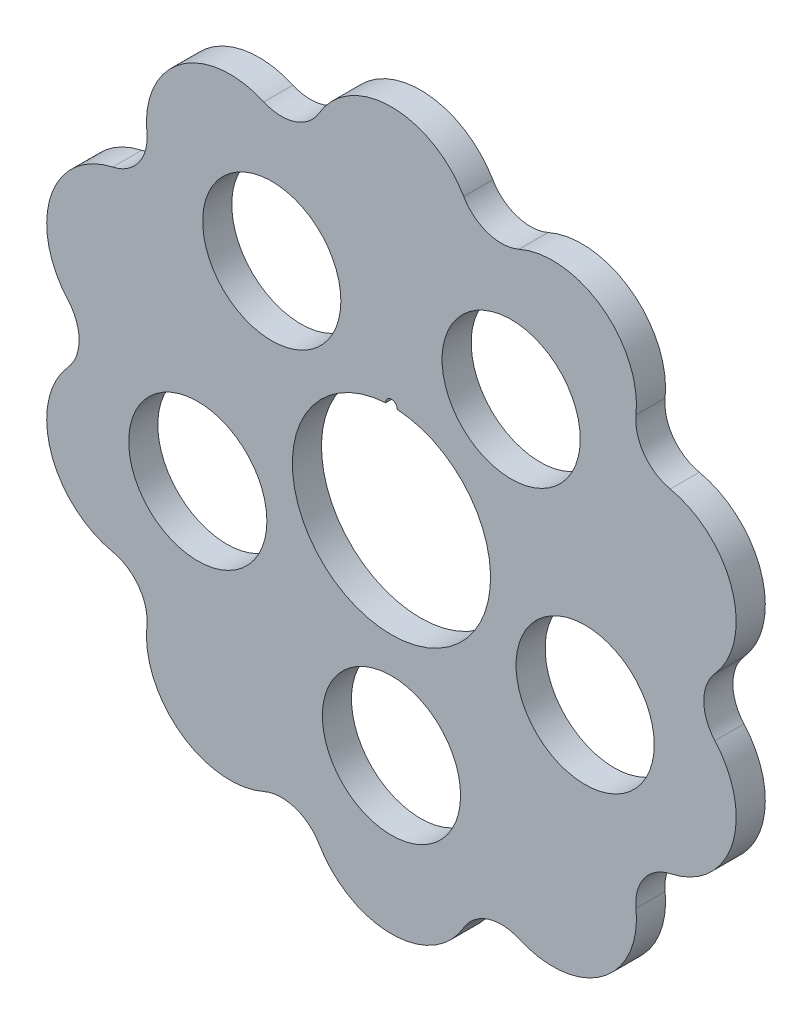
SolidWorks part; units mm, degrees
ref_plane "前视基准面" through (0, 0, 0) normal (0, 0, 1) x (1, 0, 0)
ref_plane "上视基准面" through (0, 0, 0) normal (0, 1, 0) x (1, 0, 0)
ref_plane "右视基准面" through (0, 0, 0) normal (1, 0, 0) x (0, 0, -1)
sketch "草图1" plane through (0, 0, 0) normal (0, 0, 1) x (1, 0, 0)
  line L0 (0, -37.75) -> (22.1889, -30.5404) construction
  line L1 (0, 0) -> (11.0944, -34.1452) construction
  line L2 (11.0944, -34.1452) -> (15.711, -48.3534) construction
  line L3 (0, 0) -> (0, -63.6583) construction
  line L4 (-15.1255, -46.5516) -> (0, -37.75) construction
  line L5 (0, -37.75) -> (15.1255, -46.5516) construction
  circle A0 centre (0, 0) radius 13.625
  circle A1 centre (0, 0) radius 28 construction
  circle A2 centre (0, -28) radius 9.5
  circle A3 centre (-26.6296, -8.6525) radius 9.5
  circle A4 centre (-16.458, 22.6525) radius 9.5
  circle A5 centre (16.458, 22.6525) radius 9.5
  circle A6 centre (26.6296, -8.6525) radius 9.5
  circle A7 centre (0, 0) radius 37.75 construction
  circle A8 centre (0, -37.75) radius 11.5 construction
  circle A9 centre (-22.1889, -30.5404) radius 11.5 construction
  circle A10 centre (-15.1255, -46.5516) radius 6 construction
  arc A11 (-9.9396, -43.5339) -> (9.9396, -43.5339) centre (0, -37.75) ccw
  arc A12 (9.9396, -43.5339) -> (17.5473, -41.062) centre (15.1255, -46.5516) cw
  arc A13 (-33.6299, -29.3773) -> (-17.5473, -41.062) centre (-22.1889, -30.5404) ccw
  arc A14 (-17.5473, -41.062) -> (-9.9396, -43.5339) centre (-15.1255, -46.5516) cw
  arc A15 (-44.4747, -3.9996) -> (-38.3317, -22.9059) centre (-35.9024, -11.6654) ccw
  arc A16 (-38.3317, -22.9059) -> (-33.6299, -29.3773) centre (-39.5992, -28.7705) cw
  circle A17 centre (22.1889, -30.5404) radius 11.5 construction
  circle A18 centre (0, 0) radius 42.61 construction
  circle A19 centre (15.1255, -46.5516) radius 6 construction
  circle A20 centre (35.9024, -11.6654) radius 11.5 construction
  circle A21 centre (35.9024, 11.6654) radius 11.5 construction
  circle A22 centre (22.1889, 30.5404) radius 11.5 construction
  circle A23 centre (0, 37.75) radius 11.5 construction
  circle A24 centre (-22.1889, 30.5404) radius 11.5 construction
  circle A25 centre (-35.9024, 11.6654) radius 11.5 construction
  circle A26 centre (-35.9024, -11.6654) radius 11.5 construction
  arc A27 (-38.3317, 22.9059) -> (-44.4747, 3.9996) centre (-35.9024, 11.6654) ccw
  arc A28 (-44.4747, 3.9996) -> (-44.4747, -3.9996) centre (-48.9473, 0) cw
  arc A29 (-17.5473, 41.062) -> (-33.6299, 29.3773) centre (-22.1889, 30.5404) ccw
  arc A30 (-33.6299, 29.3773) -> (-38.3317, 22.9059) centre (-39.5992, 28.7705) cw
  arc A31 (9.9396, 43.5339) -> (-9.9396, 43.5339) centre (0, 37.75) ccw
  arc A32 (-9.9396, 43.5339) -> (-17.5473, 41.062) centre (-15.1255, 46.5516) cw
  arc A33 (33.6299, 29.3773) -> (17.5473, 41.062) centre (22.1889, 30.5404) ccw
  arc A34 (17.5473, 41.062) -> (9.9396, 43.5339) centre (15.1255, 46.5516) cw
  arc A35 (44.4747, 3.9996) -> (38.3317, 22.9059) centre (35.9024, 11.6654) ccw
  arc A36 (38.3317, 22.9059) -> (33.6299, 29.3773) centre (39.5992, 28.7705) cw
  arc A37 (38.3317, -22.9059) -> (44.4747, -3.9996) centre (35.9024, -11.6654) ccw
  arc A38 (44.4747, -3.9996) -> (44.4747, 3.9996) centre (48.9473, 0) cw
  arc A39 (17.5473, -41.062) -> (33.6299, -29.3773) centre (22.1889, -30.5404) ccw
  arc A40 (33.6299, -29.3773) -> (38.3317, -22.9059) centre (39.5992, -28.7705) cw
  dimension "D1" = 27.25
  dimension "D2" = 56
  dimension "D3" = 19
  dimension "D5" = 23
  dimension "D6" = 75.5
  dimension "D8" = 85.22
  dimension "D9" = 12
  dimension "D4" = 5
  dimension "D7" = 10
  dimension "D10" = 10
extrude "凸台-拉伸1" add sketch "草图1" along normal blind 4 contours A27 A28 A15 A16 A13 A14 A11 A12 A39 A40 A37 A38 A35 A36 A33 A34 A31 A32 A29 A30
sketch "草图2" plane through (0, 0, 4) normal (0, 0, 1) x (1, 0, 0)
  circle A0 centre (0, 13.625) radius 0.8
  circle A1 centre (0, 0) radius 13.625 construction
extrude "切除-拉伸1" cut sketch "草图2" against normal blind 10
